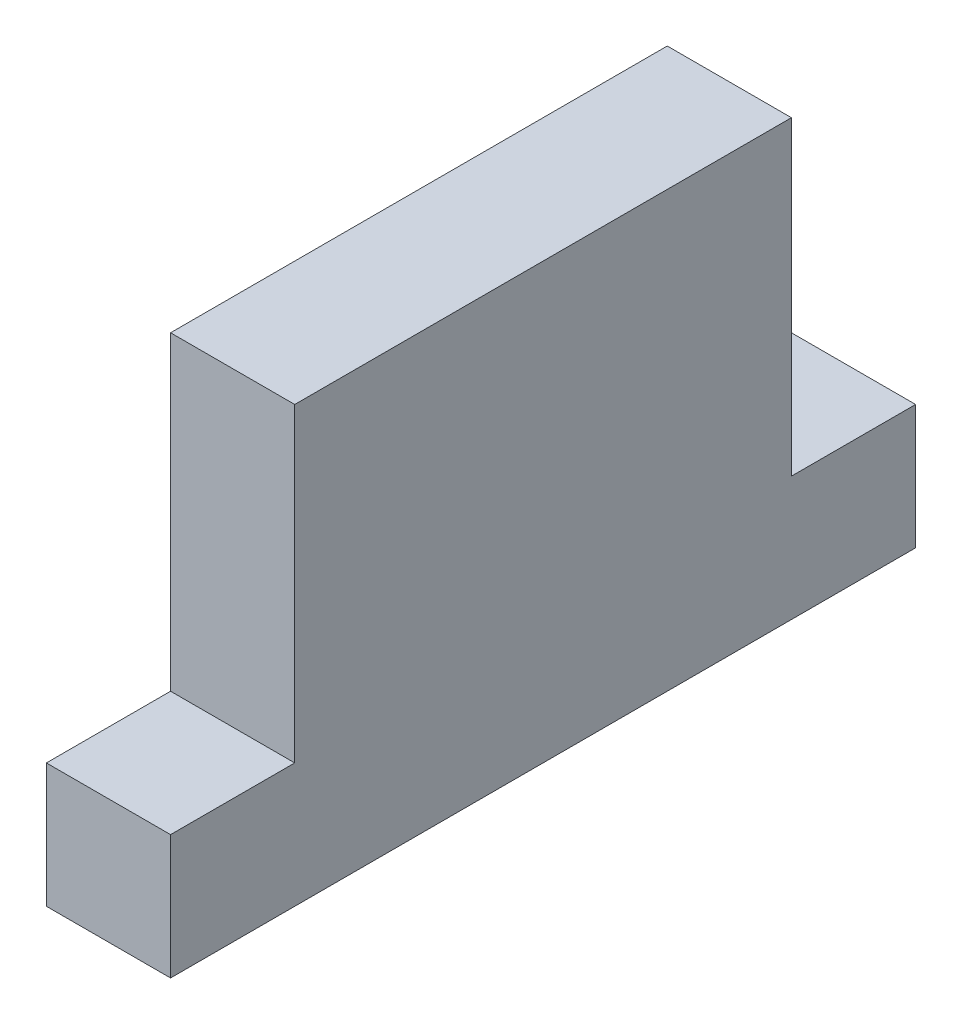
SolidWorks part; units mm, degrees
ref_plane "前视基准面" through (0, 0, 0) normal (0, 0, 1) x (1, 0, 0)
ref_plane "上视基准面" through (0, 0, 0) normal (0, 1, 0) x (1, 0, 0)
ref_plane "右视基准面" through (0, 0, 0) normal (1, 0, 0) x (0, 0, -1)
sketch "草图1" plane through (0, 0, 0) normal (0, 1, 0) x (1, 0, 0)
  line L1 (-10, 60) -> (10, 60)
  line L2 (-10, 60) -> (-10, -60)
  line L3 (-10, -60) -> (10, -60)
  line L4 (10, 60) -> (10, -60)
  line L5 (-10, 60) -> (10, -60) construction
  line L6 (-10, -60) -> (10, 60) construction
  point P0 (0, 0)
  dimension "D1" = 120
  dimension "D2" = 20
extrude "凸台-拉伸1" add sketch "草图1" along normal blind 20
sketch "草图2" plane through (10, 0, 0) normal (1, 0, 0) x (0, 0, -1)
  line L0 (0, 20) -> (40, 20)
  line L1 (-60, 20) -> (60, 20) construction
  line L2 (0, 20) -> (-40, 20)
  line L3 (-40, 20) -> (-40, 70)
  line L4 (-40, 70) -> (40, 70)
  line L5 (40, 70) -> (40, 20)
  dimension "D1" = 40
  dimension "D2" = 40
  dimension "D3" = 50
extrude "凸台-拉伸2" add sketch "草图2" against normal blind 20
